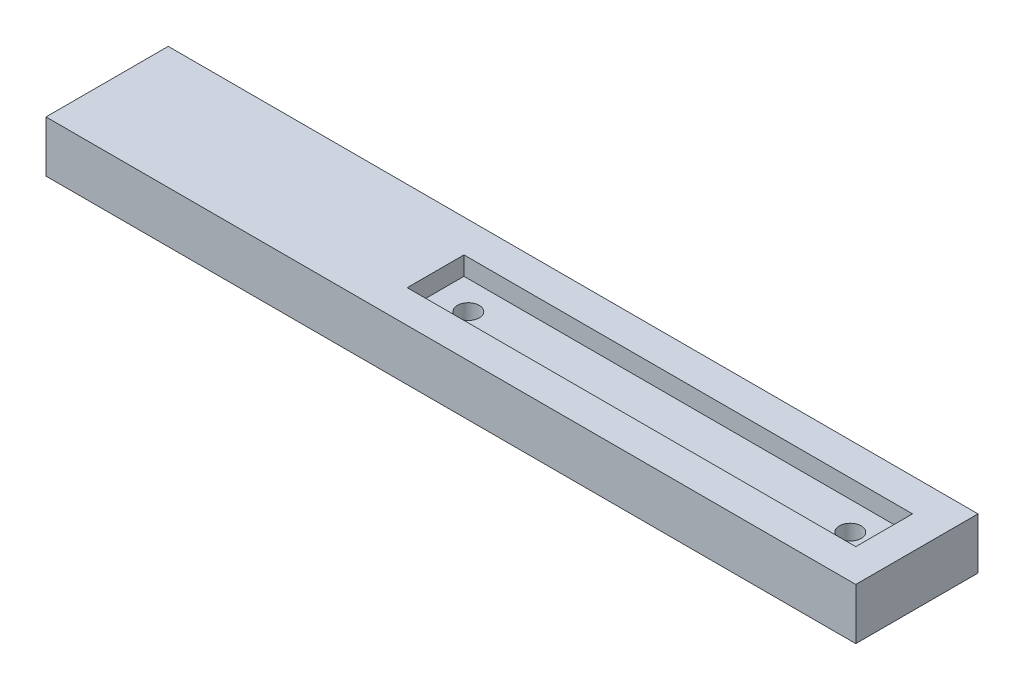
SolidWorks part; units mm, degrees
ref_plane "Front Plane" through (0, 0, 0) normal (0, 0, 1) x (1, 0, 0)
ref_plane "Top Plane" through (0, 0, 0) normal (0, 1, 0) x (1, 0, 0)
ref_plane "Right Plane" through (0, 0, 0) normal (1, 0, 0) x (0, 0, -1)
sketch "Sketch1" plane through (0, 0, 0) normal (0, 1, 0) x (1, 0, 0)
  line L0 (-37.1, 5.6) -> (37.1, 5.6)
  line L1 (-34.1, 2.6) -> (34.1, 2.6)
  line L2 (-34.1, 2.6) -> (-34.1, -2.6)
  line L3 (-34.1, -2.6) -> (34.1, -2.6)
  line L4 (34.1, 2.6) -> (34.1, -2.6)
  line L5 (-34.1, 2.6) -> (34.1, -2.6) construction
  line L6 (-34.1, -2.6) -> (34.1, 2.6) construction
  line L7 (37.1, 5.6) -> (37.1, -5.6)
  line L8 (-37.1, -5.6) -> (37.1, -5.6)
  line L9 (-37.1, 5.6) -> (-37.1, -5.6)
  point P0 (0, 0)
  dimension "D1" = 68.2
  dimension "D2" = 5.2
  dimension "D3" = 3
extrude "Boss-Extrude1" add sketch "Sketch1" against normal blind 1.7
sketch "Sketch2" plane through (0, -1.7, 0) normal (0, -1, 0) x (1, 0, 0)
  line L4 (-37.1, 5.6) -> (-37.1, -5.6)
  line L5 (-37.1, -5.6) -> (37.1, -5.6)
  line L6 (37.1, -5.6) -> (37.1, 5.6)
  line L7 (37.1, 5.6) -> (-37.1, 5.6)
  line L8 (-37.1, 5.6) -> (-37.1, -5.6)
  line L9 (-37.1, -5.6) -> (37.1, -5.6)
  line L10 (37.1, -5.6) -> (37.1, 5.6)
  line L11 (37.1, 5.6) -> (-37.1, 5.6)
  dimension "D1" = 0
extrude "Boss-Extrude2" add sketch "Sketch2" along normal blind 3
sketch "Sketch5" plane through (0, -1.7, 0) normal (0, 1, 0) x (1, 0, 0)
  line L0 (-34, 0) -> (34, 0) construction
  line L1 (-34, -2.5) -> (34, -2.5)
  line L2 (-34, -2.5) -> (-34, 2.5)
  line L3 (-34, 2.5) -> (34, 2.5)
  line L4 (34, -2.5) -> (34, 2.5)
  line L5 (-34, -2.5) -> (34, 2.5) construction
  line L6 (-34, 2.5) -> (34, -2.5) construction
  line L7 (23, 0.635) -> (28, 0.635) construction
  line L8 (23, 1.135) -> (28, 1.135)
  line L9 (23, 1.135) -> (23, 0.135)
  line L10 (23, 0.135) -> (28, 0.135)
  line L11 (28, 1.135) -> (28, 0.135)
  line L12 (23, -0.135) -> (28, -0.135)
  line L13 (23, -0.135) -> (23, -1.135)
  line L14 (23, -1.135) -> (28, -1.135)
  line L15 (28, -0.135) -> (28, -1.135)
  line L16 (23, -0.635) -> (28, -0.635) construction
  line L17 (0, 2.5) -> (0, -2.5) construction
  line L18 (20, 2.5) -> (20, -2.5) construction
  line L19 (31, 2.5) -> (31, -2.5) construction
  line L20 (-1, 2.5) -> (-1, -2.5) construction
  line L21 (-7, 2.5) -> (-7, -2.5)
  line L22 (-7, 0) -> (-1, 0) construction
  circle A0 centre (31, 0) radius 1
  circle A1 centre (0, 0) radius 1 construction
  circle A2 centre (-4, 0) radius 1
  point P0 (0, 0)
  point P37 (-8.4483, -12.9157)
  point P40 (0, 0)
  dimension "D9" = 2
  dimension "D11" = 2
  dimension "D13" = 2
  dimension "D1" = 5
  dimension "D2" = 1
  dimension "D3" = 5
  dimension "D4" = 1
  dimension "D5" = 5
  dimension "D6" = 1.27
  dimension "D7" = 20
  dimension "D8" = 3
  dimension "D10" = 3
  dimension "D12" = 6
extrude "Cut-Extrude1" cut sketch "Sketch5" against normal up to surface (3 mm away) contours A2 | A0 up to face at (0, -4.7, 0)
sketch "Sketch7" plane through (0, -4.7, 0) normal (0, -1, 0) x (1, 0, 0)
  line L0 (-5.15, 1.9919) -> (-6.3, 0)
  line L1 (-2.85, -1.9919) -> (-1.7, 0)
  line L2 (-1.7, 0) -> (-2.85, 1.9919)
  line L3 (-2.85, 1.9919) -> (-5.15, 1.9919)
  line L4 (-6.3, 0) -> (-5.15, -1.9919)
  line L5 (-5.15, -1.9919) -> (-2.85, -1.9919)
  line L7 (33.3, 0) -> (32.15, 1.9919)
  line L8 (32.15, 1.9919) -> (29.85, 1.9919)
  line L9 (29.85, 1.9919) -> (28.7, 0)
  line L10 (28.7, 0) -> (29.85, -1.9919)
  line L11 (29.85, -1.9919) -> (32.15, -1.9919)
  line L12 (32.15, -1.9919) -> (33.3, 0)
  circle A0 centre (-4, 0) radius 2.3 construction
  circle A1 centre (31, 0) radius 2.3 construction
  dimension "D1" = 4.6
  dimension "D2" = 4.6
extrude "Cut-Extrude2" cut sketch "Sketch7" against normal blind 1.6
sketch "Sketch8" plane through (0, -1.7, 0) normal (0, 1, 0) x (1, 0, 0)
  line L1 (-7, 2.6) -> (-7, -2.6)
  line L2 (34.1, 2.6) -> (-34.1, 2.6) construction
  line L3 (-34.1, -2.6) -> (34.1, -2.6) construction
  line L4 (-7, 2.5) -> (-7, -2.5) construction
  line L5 (-7, 2.6) -> (-34.1, 2.6)
  line L6 (-34.1, 2.6) -> (-34.1, -2.6)
  line L7 (-34.1, -2.6) -> (-7, -2.6)
extrude "Boss-Extrude3" add sketch "Sketch8" along normal up to surface (1.7 mm away) up to face at (0, 0, 0)
